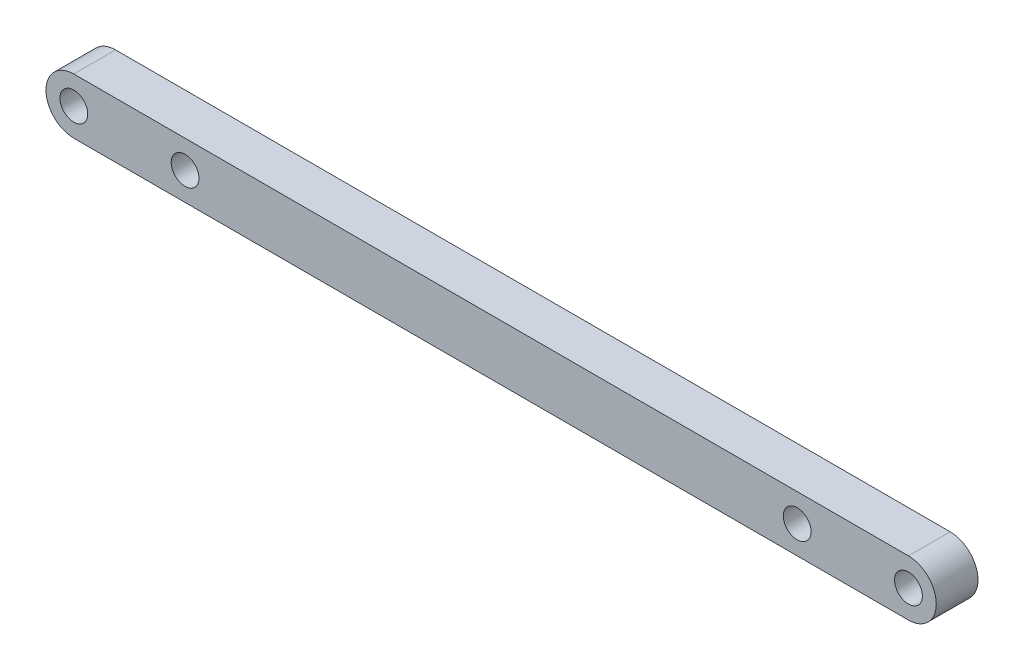
SolidWorks part; units mm, degrees
ref_plane "Front Plane" through (0, 0, 0) normal (0, 0, 1) x (1, 0, 0)
ref_plane "Top Plane" through (0, 0, 0) normal (0, 1, 0) x (1, 0, 0)
ref_plane "Right Plane" through (0, 0, 0) normal (1, 0, 0) x (0, 0, -1)
sketch "Sketch1" plane through (0, 0, 0) normal (0, 0, 1) x (1, 0, 0)
  line L0 (0, 0) -> (60, 0) construction
  line L1 (0, 2) -> (60, 2)
  line L2 (0, -2) -> (60, -2)
  line L3 (30, 2) -> (30, -2) construction
  arc A0 (0, 2) -> (0, -2) centre (0, 0) ccw
  arc A1 (60, -2) -> (60, 2) centre (60, 0) ccw
  circle A2 centre (0, 0) radius 1
  circle A3 centre (8, 0) radius 1
  circle A4 centre (52, 0) radius 1
  circle A5 centre (60, 0) radius 1
  point P3 (30, 0)
  dimension "D2" = 2
  dimension "D3" = 2
  dimension "D1" = 60
  dimension "D4" = 8
extrude "Boss-Extrude1" add sketch "Sketch1" along normal blind 3
